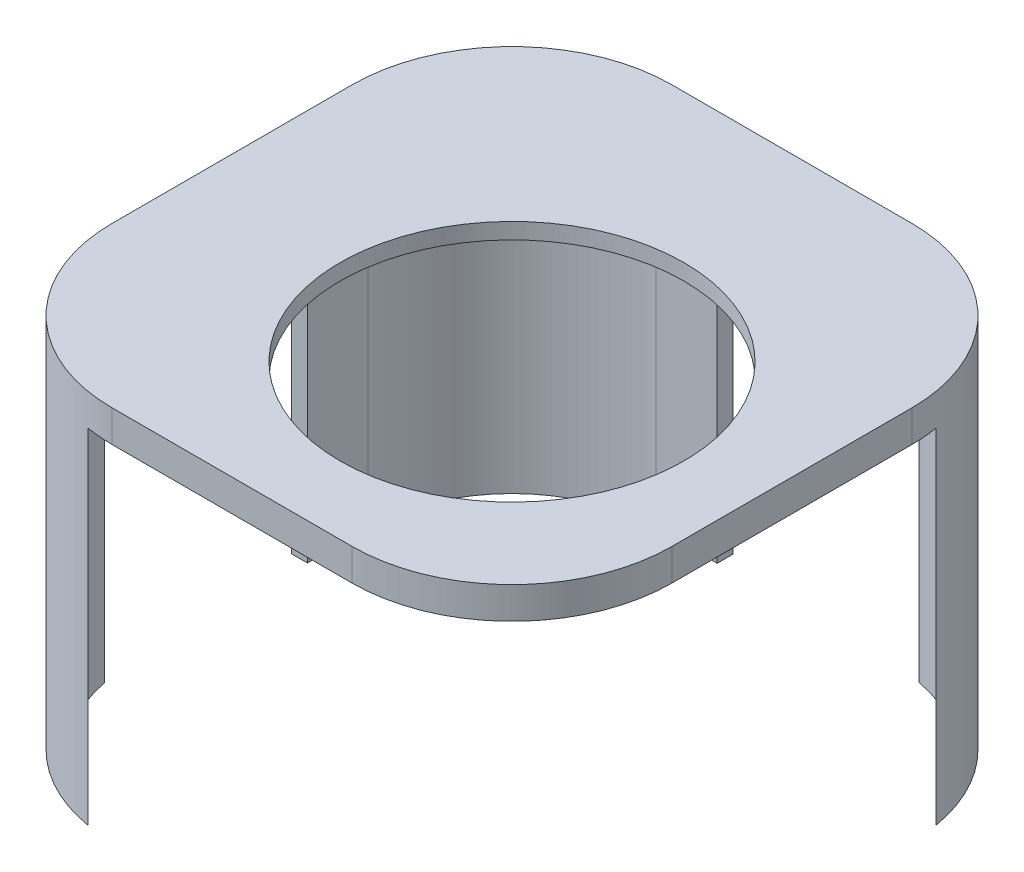
SolidWorks part; units mm, degrees
ref_plane "Front Plane" through (0, 0, 0) normal (0, 0, 1) x (1, 0, 0)
ref_plane "Top Plane" through (0, 0, 0) normal (0, 1, 0) x (1, 0, 0)
ref_plane "Right Plane" through (0, 0, 0) normal (1, 0, 0) x (0, 0, -1)
sketch "Sketch1" plane through (0, 0, 0) normal (0, 1, 0) x (1, 0, 0)
  line L1 (-35, -35) -> (35, -35)
  line L2 (-35, -35) -> (-35, 35)
  line L3 (-35, 35) -> (35, 35)
  line L4 (35, -35) -> (35, 35)
  line L5 (-35, -35) -> (35, 35) construction
  line L6 (-35, 35) -> (35, -35) construction
  point P0 (0, 0)
  dimension "D1" = 70
extrude "Boss-Extrude1" add sketch "Sketch1" along normal blind 47
fillet "Fillet1" radius 20 4 edges at (35, 23.5, 35) (-35, 23.5, 35) (-35, 23.5, -35) (35, 23.5, -35)
shell "Shell1" thickness 2
sketch "Sketch2" plane through (0, 47, 0) normal (0, 1, 0) x (1, 0, 0)
  circle A0 centre (5, -5) radius 21.5
  dimension "D1" = 43
extrude "Cut-Extrude1" cut sketch "Sketch2" against normal through all
ref_plane "Plane2" through (0, 0, 0) normal (0.7071, 0, 0.7071) x (0.7071, 0, -0.7071)
sketch "Sketch6" plane through (0, 0, 0) normal (0.7071, 0, 0.7071) x (0.7071, 0, -0.7071)
  line L1 (-37.5, 43.0242) -> (37.5, 43.0242)
  line L2 (-37.5, 43.0242) -> (-37.5, 0)
  line L3 (-37.5, 0) -> (37.5, 0)
  line L4 (37.5, 43.0242) -> (37.5, 0)
  line L5 (-37.5, 43.0242) -> (37.5, 0) construction
  line L6 (-37.5, 0) -> (37.5, 43.0242) construction
  point P0 (0, 21.5121)
  point P5 (0, 43.0242)
  dimension "D1" = 75
extrude "Cut-Extrude4" cut sketch "Sketch6" along normal through all
sketch "Sketch7" plane through (0, 0, -35) normal (0, 0, -1) x (-1, 0, 0)
  line L0 (-15, 0) -> (15, 0) construction
  line L1 (7.3352, 0) -> (-18.2135, 0)
  line L2 (7.3352, 0) -> (7.3352, 28.8008)
  line L3 (7.3352, 28.8008) -> (-18.2135, 28.8008)
  line L4 (-18.2135, 0) -> (-18.2135, 28.8008)
extrude "Cut-Extrude5" cut sketch "Sketch7" against normal blind 10
sketch "Sketch9" plane through (-35, 0, 0) normal (-1, 0, 0) x (0, 0, 1)
  line L0 (-15, 0) -> (15, 0) construction
  line L1 (-7.4103, 0) -> (18.2618, 0)
  line L2 (-7.4103, 0) -> (-7.4103, 28.5605)
  line L3 (-7.4103, 28.5605) -> (18.2618, 28.5605)
  line L4 (18.2618, 0) -> (18.2618, 28.5605)
extrude "Cut-Extrude6" cut sketch "Sketch9" against normal blind 10 contours L2 L3 L4 L1
